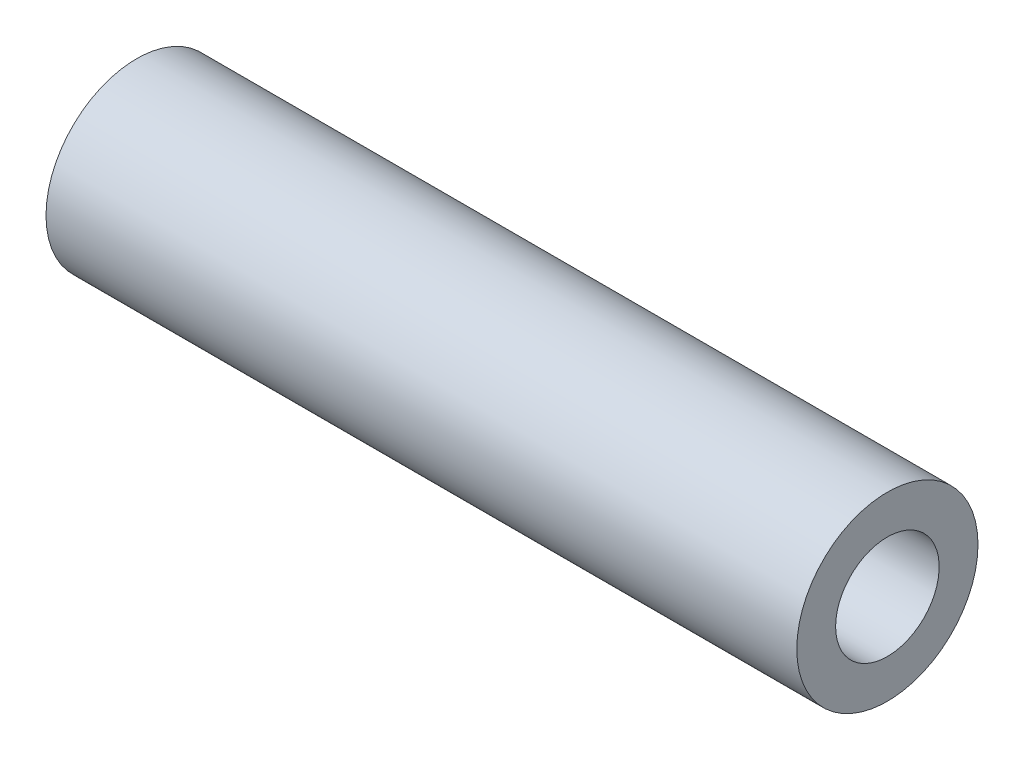
SolidWorks part; units mm, degrees
material "ﾎﾟﾘｵｷｼﾒﾁﾚﾝ(POM)ｱｾﾀｰﾙ共重合体"
ref_plane "正面" through (0, 0, 0) normal (0, 0, 1) x (1, 0, 0)
ref_plane "平面" through (0, 0, 0) normal (0, 1, 0) x (1, 0, 0)
ref_plane "右側面" through (0, 0, 0) normal (1, 0, 0) x (0, 0, -1)
sketch "ｽｹｯﾁ1" plane through (0, 0, 0) normal (0, 0, 1) x (1, 0, 0)
  line L0 (0, 0) -> (50000, 0) construction
  line L1 (-29, 7) -> (29, 7)
  line L2 (-29, 7) -> (-29, 4)
  line L3 (-29, 4) -> (29, 4)
  line L4 (29, 7) -> (29, 4)
  point P4 (0, 7)
  dimension "D1" = 58
  dimension "D2" = 8
  dimension "D3" = 14
revolve "回転1" add sketch "ｽｹｯﾁ1" angle 360 about L0
